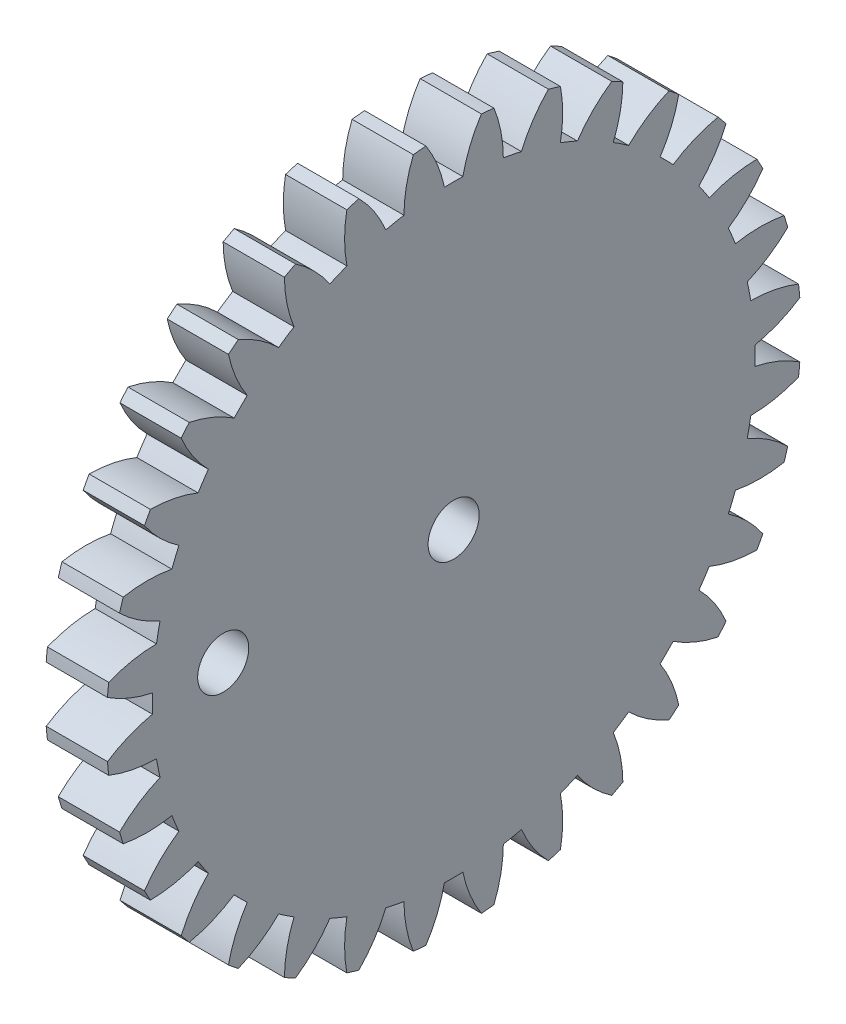
SolidWorks part; units mm, degrees
ref_plane "Plane1" through (0, 0, 0) normal (0, 0, 1) x (1, 0, 0)
ref_plane "Plane2" through (0, 0, 0) normal (0, 1, 0) x (1, 0, 0)
ref_plane "Plane3" through (0, 0, 0) normal (1, 0, 0) x (0, 0, -1)
sketch "HoldingSke" plane through (0, 0, 0) normal (0, 1, 0) x (1, 0, 0)
  line L0 (0, 0) -> (0.212, -0.1325)
  line L1 (-15, 0) -> (100, 0) construction
  line L2 (0, 0) -> (-2.1039, 2.3779)
  line L3 (0, 0) -> (-11.863, 4.5341)
  line L4 (0, 0) -> (7.3237, 4.5764)
  line L5 (0, 0) -> (-46.8476, -17.4728)
  line L6 (0, 0) -> (-9.9476, -6.7116)
  line L7 (-2.1039, 2.3779) -> (8.6586, 51.2059)
  line L8 (-76.2, 54.61) -> (-74.4, 54.61)
  line L9 (-71.009, 38.7566) -> (-53.1078, 45.2721)
  line L10 (-76.2, 71.12) -> (104.1128, 71.12)
  line L11 (0, 0) -> (-12, 0)
  line L12 (-76.2, 101.6) -> (-76.073, 101.6)
  line L13 (24.9733, 27.94) -> (52.9518, 28.4284)
  line L14 (24.9733, 27.94) -> (24.9743, 27.94)
  line L15 (24.9733, 27.94) -> (100.4006, 29.5858)
  line L16 (-63.627, -4) -> (-12.827, -4)
  circle A0 centre (0, 0) radius 5
  circle A1 centre (0, 0) radius 37.5
  circle A2 centre (0, 0) radius 37.5
  circle A3 centre (0, 0) radius 5
  dimension "MHD" = 75
  dimension "Hub_dia" = 75
  dimension "Bore" = 10
  dimension "MBD" = 10
  dimension "Num_teeth" = 32
  dimension "Pitch" = 0.25
  dimension "Overall_len" = 50
  dimension "Show_teeth" = 32
  dimension "Thickness" = 12
  dimension "OAL" = 50.0001
  dimension "T_dim" = 1.8
  dimension "Ap" = 20
  dimension "H" = 19.05
  dimension "Pitch_radius" = 180.3128
  dimension "Width" = 12
  dimension "Backlash" = 0.127
  dimension "Addendum_fac" = 1
  dimension "Dedendum_fac" = 1.25
  dimension "Clearance_fac" = 0.25
  dimension "Dedendum_add" = 0.001
  dimension "Module" = 4
sketch "BasProSke" plane through (0, 0, 0) normal (0, 1, 0) x (1, 0, 0)
  line L0 (-10, 0) -> (60, 0) construction
  line L1 (0, 0) -> (0, 68)
  line L2 (0, 0) -> (12, 0)
  line L3 (12, 0) -> (12, 68)
  line L4 (12, 68) -> (0, 68)
  dimension "Thickness" = 12
  dimension "Diameter" = 136
revolve "Base-Revolve" add sketch "BasProSke" angle 360 about L0
sketch "TooCutSke" plane through (0, 0, 0) normal (1, 0, 0) x (0, 0, -1)
  line L1 (0, 0) -> (0, 107) construction
  line L2 (0, 0) -> (-3.3625, 63.9116) construction
  line L3 (0, 0) -> (-12.5331, 127.2512) construction
  line L4 (-3.3625, 63.9116) -> (-6.2666, 63.6256) construction
  arc A0 (1.8084, 58.9713) -> (-1.8084, 58.9713) centre (0, 0) ccw
  arc A1 (5.4528, 67.8065) -> (-5.4528, 67.8065) centre (0, 0) ccw
  circle A2 centre (0, 0) radius 64 construction
  circle A3 centre (0, 0) radius 60.1403 construction
  arc A4 (-1.8084, 58.9713) -> (-5.4528, 67.8065) centre (-26.8804, 53.7987) ccw
  arc A5 (5.4528, 67.8065) -> (1.8084, 58.9713) centre (26.8804, 53.7987) ccw
  dimension "Root_dia" = 117.998
  dimension "Overcut_dia" = 136.0508
  dimension "Pitch_dia" = 128
  dimension "Base_dia" = 120.2807
  dimension "Flank_rad" = 25.6
  dimension "Half_ang" = 5.625
  dimension "Half_CT" = 2.9181
extrude "ToothCut" cut sketch "TooCutSke" along normal through all
fillet "Breaks" [suppressed] radius 0.08
fillet "RootFillets" [suppressed] radius 1.001
pattern_circular "TeethCuts" count 32 every 11.25 about axis through (-10, 0, 0) along (1, 0, 0) of "ToothCut", "RootFillets", "Breaks"
sketch "HubNeaOneSke" plane through (0, 0, 0) normal (-1, 0, 0) x (0, 0, 1)
  circle A0 centre (0, 0) radius 37.5
  dimension "Diameter" = 75
extrude "HubNearOne" [suppressed] add sketch "HubNeaOneSke" along normal blind 38.0001
sketch "HubNeaBotSke" plane through (0, 0, 0) normal (-1, 0, 0) x (0, 0, 1)
  circle A0 centre (0, 0) radius 37.5
  dimension "Diameter" = 75
extrude "HubNearBoth" [suppressed] add sketch "HubNeaBotSke" along normal blind 19
ref_plane "FarPln" through (12, 0, 0) normal (1, 0, 0) x (0, 0, -1)
sketch "HubFarSke" plane through (12, 0, 0) normal (1, 0, 0) x (0, 0, -1)
  circle A0 centre (0, 0) radius 37.5
  dimension "Diameter" = 75
extrude "HubFar" [suppressed] add sketch "HubFarSke" along normal blind 19
sketch "BorSke" plane through (0, 0, 0) normal (1, 0, 0) x (0, 0, -1)
  circle A0 centre (0, 0) radius 5
  dimension "Diameter" = 10
extrude "Bore" cut sketch "BorSke" along normal mid plane 100.0001
sketch "KeySke" plane through (0, 0, 0) normal (1, 0, 0) x (0, 0, -1)
  line L0 (-2, 0) -> (-2, 6.8)
  line L1 (-2, 6.8) -> (2, 6.8)
  line L2 (2, 6.8) -> (2, 0)
  line L3 (0, 0) -> (0, 34) construction
  line L4 (-2, 0) -> (2, 0)
  dimension "Offset" = 6.8
  dimension "Width" = 4
extrude "Keyway" [suppressed] cut sketch "KeySke" along normal mid plane 100.0001
pattern_circular "Keyway2" [suppressed] count 2 every 90 about axis through (-10, 0, 0) along (1, 0, 0)
sketch "草图2" plane through (12, 0, 0) normal (1, 0, 0) x (0, 0, -1)
  circle A0 centre (-45.1198, 0) radius 5
extrude "切除-拉伸3" cut sketch "草图2" against normal through all
equation "' \"Module@HoldingSke\" = 6.35"
equation "' \"Num_teeth@HoldingSke\" = 12"
equation "' \"Ap@HoldingSke\" =  20"
equation "' \"Ap@HoldingSke\" = 20"
equation "' \"Width@HoldingSke\" = 0.5 * 25.4"
equation "' \"Hub_dia@HoldingSke\"= 1 * 25.4"
equation "' \"Hub_dia@HoldingSke\" = 1 * 25.4"
equation "' \"Overall_len@HoldingSke\" = 1.0 * 25.4"
equation "' \"Bore@HoldingSke\" = 0.75 * 25.4"
equation "' \"T_dim@HoldingSke\" = 0.1 * 25.4"
equation "' \"Width@KeySke\" = 0.25 * 25.4"
equation "' \"Show_teeth@HoldingSke\" = 13"
equation "' \"Backlash@HoldingSke\" = 0.009 * 25.4"
equation "' \"Addendum_fac@HoldingSke\" = 1.0"
equation "' \"Dedendum_fac@HoldingSke\" = 1.25"
equation "' \"Dedendum_add@HoldingSke\" = 0.00005 * 25.4"
equation "' \"Clearance_fac@HoldingSke\" = 0.25"
equation "\"Pitch@HoldingSke\" = 1 / \"Module@HoldingSke\""
equation "\"Overcut_dia@TooCutSke\" = (\"Num_teeth@HoldingSke\" + 2 * \"Addendum_fac@HoldingSke\") / \"Pitch@HoldingSke\" + 0.002 * 25.4"
equation "\"Pitch_dia@TooCutSke\" = \"Num_teeth@HoldingSke\" / \"Pitch@HoldingSke\""
equation "\"Base_dia@TooCutSke\" = \"Num_teeth@HoldingSke\" / \"Pitch@HoldingSke\" * cos((\"Ap@HoldingSke\"  * 3.14159265 / 180))"
equation "\"Root_dia@TooCutSke\" = (\"Num_teeth@HoldingSke\" + 2) / \"Pitch@HoldingSke\" - 2 * (\"Addendum_fac@HoldingSke\" + \"Dedendum_fac@HoldingSke\") / \"Pitch@HoldingSke\" - \"Dedendum_add@HoldingSke\" * 2"
equation "\"Half_ang@TooCutSke\" = 180 / \"Num_teeth@HoldingSke\""
equation "\"Half_CT@TooCutSke\" = \"Num_teeth@HoldingSke\" / \"Pitch@HoldingSke\" * sin((3.14159265 / 2 / \"Num_teeth@HoldingSke\")) / 2 - 7 * \"Backlash@HoldingSke\" / 4"
equation "\"Flank_rad@TooCutSke\" = \"Num_teeth@HoldingSke\" / \"Pitch@HoldingSke\" / 5"
equation "\"Radius@RootFillets\" = \"Clearance_fac@HoldingSke\" / \"Pitch@HoldingSke\" + \"Dedendum_add@HoldingSke\""
equation "\"Break_rad@Breaks\" = 0.02 / \"Pitch@HoldingSke\""
equation "\"Thickness@HoldingSke\" = \"Width@HoldingSke\""
equation "\"OAL@HoldingSke\" = \"Thickness@HoldingSke\""
equation "\"MHD@HoldingSke\" = (\"Num_teeth@HoldingSke\" + 2) / \"Pitch@HoldingSke\" - 2 * (\"Addendum_fac@HoldingSke\" + \"Dedendum_fac@HoldingSke\")  / \"Pitch@HoldingSke\" - \"Dedendum_add@HoldingSke\" * 2"
equation "\"MBD@HoldingSke\" = (\"Num_teeth@HoldingSke\" + 2) / \"Pitch@HoldingSke\" - 2 * (\"Addendum_fac@HoldingSke\" + \"Dedendum_fac@HoldingSke\")  / \"Pitch@HoldingSke\" - \"Dedendum_add@HoldingSke\" * 2 - 0.002 * 25.4"
equation "\"MHD@HoldingSke\" = ((sgn( \"MHD@HoldingSke\" - \"Hub_dia@HoldingSke\" )-1)*( \"MHD@HoldingSke\" - \"Hub_dia@HoldingSke\" ))/-2+ \"Hub_dia@HoldingSke\""
equation "\"MBD@HoldingSke\" = ((sgn( \"MBD@HoldingSke\" - \"Bore@HoldingSke\" )-1)*( \"MBD@HoldingSke\" - \"Bore@HoldingSke\" ))/-2+ \"Bore@HoldingSke\""
equation "\"OAL@HoldingSke\" = ((sgn( \"OAL@HoldingSke\" - \"Overall_len@HoldingSke\" )+1)*( \"OAL@HoldingSke\" - \"Overall_len@HoldingSke\" ))/2 + \"Overall_len@HoldingSke\" + 0.000002 * 25.4"
equation "\"Num_teeth@TeethCuts\" = int( \"Show_teeth@HoldingSke\" ) + 1"
equation "\"Num_teeth@TeethCuts\" = ((sgn( \"Num_teeth@TeethCuts\" - \"Num_teeth@HoldingSke\" )-1)*( \"Num_teeth@TeethCuts\" - \"Num_teeth@HoldingSke\" ))/-2+ \"Num_teeth@HoldingSke\""
equation "\"Num_teeth@TeethCuts\" = ((sgn( \"Num_teeth@TeethCuts\" - 2.0)+1)*( \"Num_teeth@TeethCuts\" - 2.0))/2 +2.0"
equation "\"Angle@TeethCuts\" = 360.0 / \"Num_teeth@HoldingSke\""
equation "\"Diameter@BasProSke\" = (\"Num_teeth@HoldingSke\" + 2 * \"Addendum_fac@HoldingSke\") / \"Pitch@HoldingSke\""
equation "\"Thickness@BasProSke\"  = \"Thickness@HoldingSke\""
equation "' \"Fillet_rad@BasProSke\" =  \"Thickness@HoldingSke\" * 0.05"
equation "' \"Fillet_rad@BasProSke\" = \"Thickness@HoldingSke\" * 0.05"
equation "\"MHD@HoldingSke\" = ((sgn( \"MHD@HoldingSke\" - \"Root_dia@TooCutSke\" )-1)*( \"MHD@HoldingSke\" - \"Root_dia@TooCutSke\" ))/-2+ \"Root_dia@TooCutSke\""
equation "\"Diameter@HubNeaOneSke\" = \"MHD@HoldingSke\""
equation "\"Length@HubNearOne\" = \"OAL@HoldingSke\" - \"Thickness@BasProSke\""
equation "\"Diameter@HubNeaBotSke\" = \"MHD@HoldingSke\""
equation "\"Length@HubNearBoth\" = ( \"OAL@HoldingSke\" - \"Thickness@BasProSke\" ) / 2.0"
equation "\"Thickness@FarPln\" = \"Thickness@BasProSke\""
equation "\"Diameter@HubFarSke\" = \"MHD@HoldingSke\""
equation "\"Length@HubFar\" = ( \"OAL@HoldingSke\" - \"Thickness@BasProSke\" ) / 2.0"
equation "\"Diameter@BorSke\" = \"MBD@HoldingSke\""
equation "\"D1@Bore\" = \"OAL@HoldingSke\" * 2.0"
equation "\"D1@Keyway\" = \"OAL@HoldingSke\" * 2.0"
equation "\"Offset@KeySke\" = \"T_dim@HoldingSke\" + \"MBD@HoldingSke\" / 2.0"
